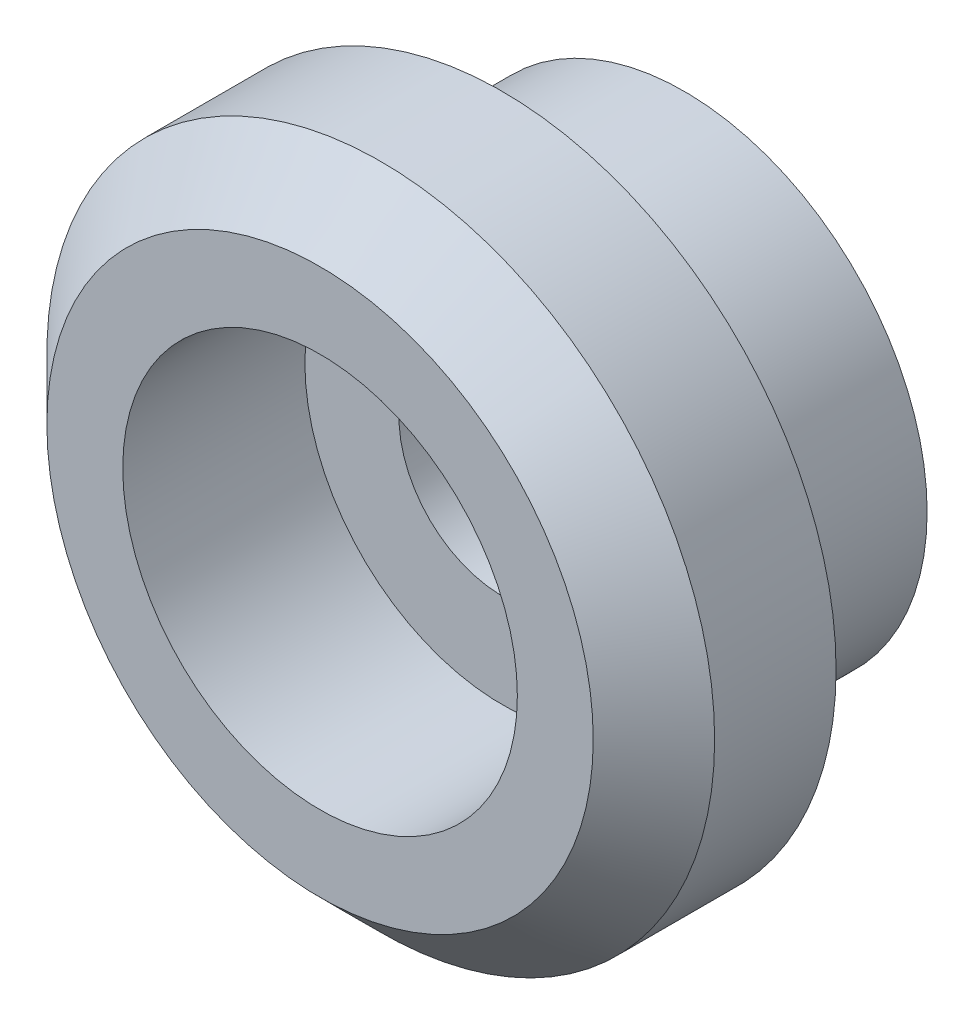
SolidWorks part; units mm, degrees
material "PE High Density"
ref_plane "Front Plane" through (0, 0, 0) normal (0, 0, 1) x (1, 0, 0)
ref_plane "Top Plane" through (0, 0, 0) normal (0, 1, 0) x (1, 0, 0)
ref_plane "Right Plane" through (0, 0, 0) normal (1, 0, 0) x (0, 0, -1)
sketch "Sketch1" plane through (0, 0, 0) normal (0, 0, 1) x (1, 0, 0)
  circle A0 centre (0, 0) radius 4
  dimension "D1" = 8
extrude "Boss-Extrude1" add sketch "Sketch1" along normal blind 3
sketch "Sketch2" plane through (0, 0, 3) normal (0, 0, 1) x (1, 0, 0)
  circle A0 centre (0, 0) radius 5.5
  dimension "D1" = 11
extrude "Boss-Extrude2" add sketch "Sketch2" along normal blind 3
hole_wizard "CBORE for M3 SHCS1" positions "Sketch5" profile "Sketch6" counterbore size "M3" standard "Ansi Metric" end condition through all
sketch "Sketch5" plane through (0, 0, 6) normal (0, 0, 1) x (1, 0, 0)
  point P0 (0, 0)
sketch "Sketch6" plane through (0, 0, 6) normal (1, 0, 0) x (0, -1, 0)
  line L0 (0, 0) -> (0, 6)
  line L1 (0, 6) -> (1.7, 6)
  line L3 (1.7, 6) -> (1.7, 3)
  line L4 (1.7, 3) -> (3.25, 3)
  line L5 (3.25, 3) -> (3.25, 0)
  line L7 (3.25, 0) -> (0, 0)
  line L11 (0, -6.35) -> (0, 107.95) construction
  dimension "Thru Hole Dia." = 3.4
  dimension "Thru Hole Depth" = 6
  dimension "C'Bore Dia." = 6.5
  dimension "C'Bore Depth" = 3
chamfer "Chamfer1" distance 1 angle 45 1 edges at (5.5, 0, 6)
